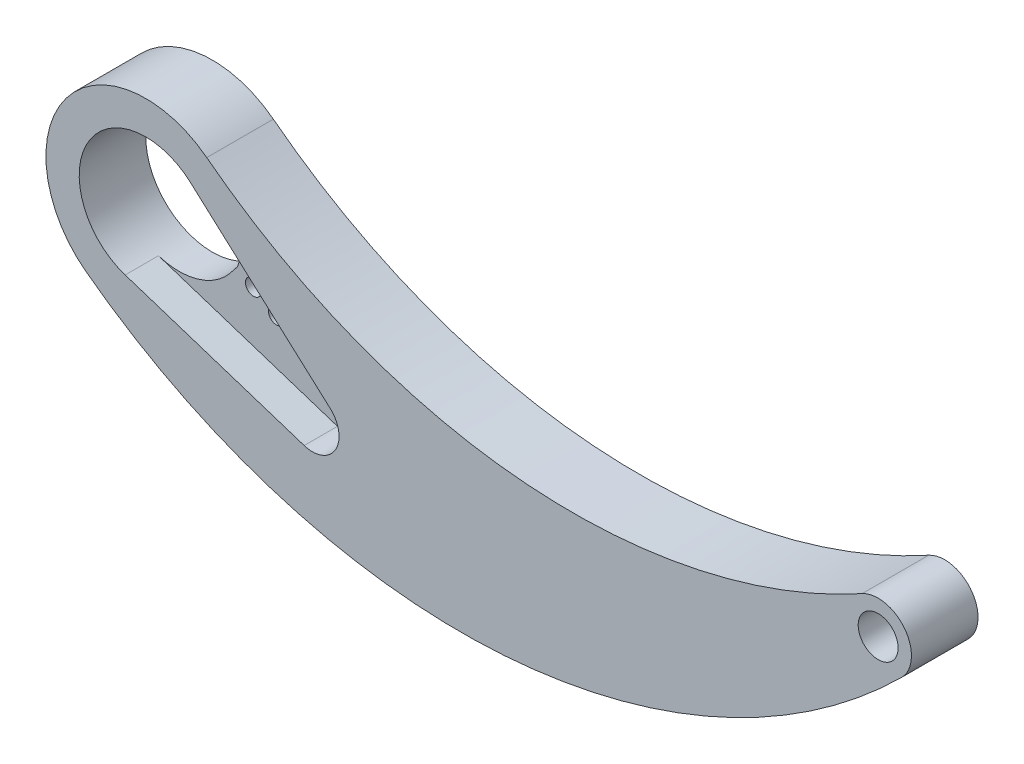
SolidWorks part; units mm, degrees
ref_plane "Front Plane" through (0, 0, 0) normal (0, 0, 1) x (1, 0, 0)
ref_plane "Top Plane" through (0, 0, 0) normal (0, 1, 0) x (1, 0, 0)
ref_plane "Right Plane" through (0, 0, 0) normal (1, 0, 0) x (0, 0, -1)
sketch "Sketch1" plane through (0, 0, 0) normal (0, 0, 1) x (1, 0, 0)
  line L0 (0, 0) -> (55, 0) construction
  line L2 (0, 0) -> (-4.5534, 0) construction
  circle A2 centre (55, 0) radius 1.5
  circle A3 centre (0, 0) radius 5
  arc A4 (4.5779, 5.9408) -> (53.7919, 2.1887) centre (32.0455, 41.5853) ccw
  arc A5 (-4.4965, -6.0026) -> (56.7594, -1.776) centre (23.6818, 31.6136) ccw
  circle A6 centre (0, 0) radius 7.5
  circle A7 centre (55, 0) radius 2.5
  dimension "D2" = 55
  dimension "D3" = 10
  dimension "D4" = 3
  dimension "D5" = 45
  dimension "D1" = 15
  dimension "D7" = 47
  dimension "D8" = 5
  dimension "D6" = 180
extrude "Boss-Extrude1" add sketch "Sketch1" along normal blind 5 contours A7 A4 A6 A5 | A6 A3 | A7 A2
sketch "Sketch2" plane through (0, 0, 5) normal (0, 0, 1) x (1, 0, 0)
  line L0 (0, 0) -> (3.8538, -2.225) construction
  line L1 (0, 0) -> (7.8138, 0) construction
  circle A0 centre (3.8538, -2.225) radius 0.6
  circle A6 centre (5.5859, -3.225) radius 0.6
  circle A7 centre (7.3179, -4.225) radius 0.6
  circle A8 centre (9.05, -5.225) radius 0.6
  circle A9 centre (10.782, -6.225) radius 0.6
  circle A10 centre (12.5141, -7.225) radius 0.6
  dimension "D2" = 1.2
  dimension "D1" = 30
  dimension "D3" = 4.45
  dimension "D4" = 6
extrude "Cut-Extrude1" cut sketch "Sketch2" against normal blind 10
sketch "Sketch3" plane through (0, 0, 5) normal (0, 0, 1) x (1, 0, 0)
  line L0 (3.3445, 3.7167) -> (13.8519, -5.7383)
  line L1 (0, 0) -> (12.5141, -7.225) construction
  line L2 (-1.5465, -4.7548) -> (11.8955, -9.1269)
  circle A0 centre (12.5141, -7.225) radius 2
  circle A1 centre (0, 0) radius 5
  arc A2 (4.4516, -2.2767) -> (4.1975, -2.7168) centre (0, 0) ccw construction
  dimension "D1" = 4
extrude "Cut-Extrude2" cut sketch "Sketch3" against normal blind 2.5
